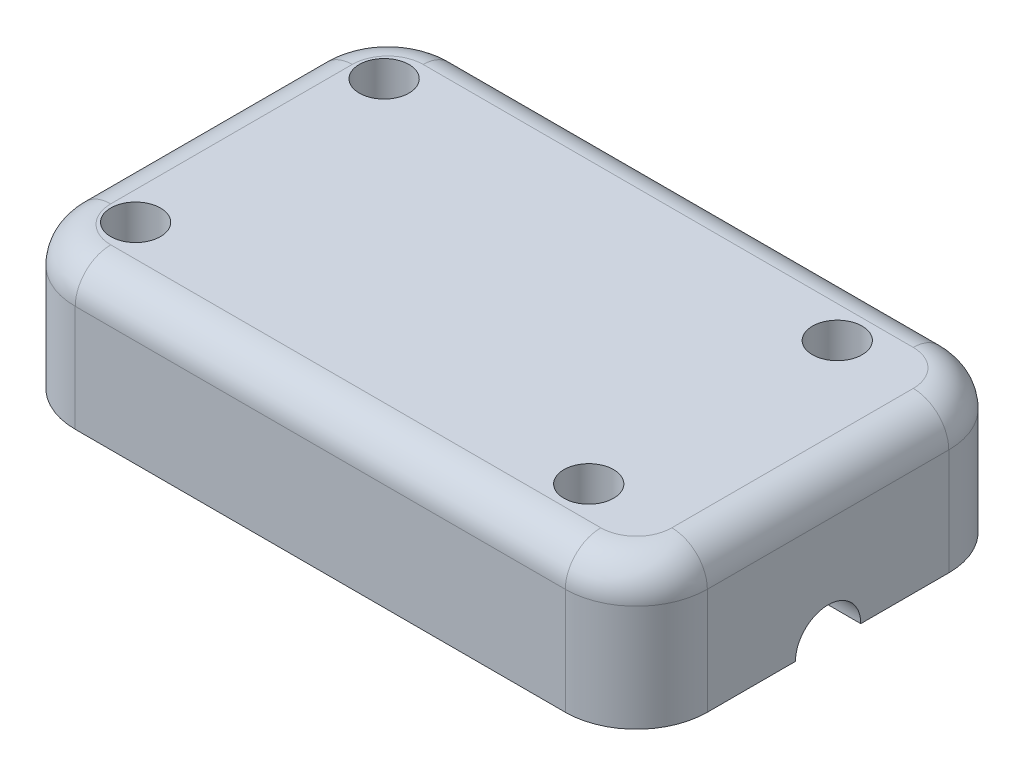
SolidWorks part; units mm, degrees
ref_plane "Front Plane" through (0, 0, 0) normal (0, 0, 1) x (1, 0, 0)
ref_plane "Top Plane" through (0, 0, 0) normal (0, 1, 0) x (1, 0, 0)
ref_plane "Right Plane" through (0, 0, 0) normal (1, 0, 0) x (0, 0, -1)
sketch "Sketch1" plane through (-2.183, 0, 0) normal (1, 0, 0) x (0, 0, -1)
  line L0 (30.2029, 27.775) -> (30.2029, 26.275) construction
  line L1 (72.2029, 27.775) -> (72.2029, 26.275) construction
  line L2 (30.2029, 27.775) -> (30.2029, 26.275)
  line L3 (72.2029, 27.775) -> (72.2029, 26.275)
  line L4 (51.2113, 25.275) -> (30.2029, 25.275)
  line L5 (51.2113, 25.275) -> (72.2029, 25.275)
  line L6 (52.7529, 43.575) -> (53.6129, 43.575) construction
  line L7 (52.7529, 43.575) -> (53.6129, 43.575)
  line L8 (72.2029, 25.275) -> (72.2029, 43.275)
  line L9 (72.2029, 25.275) -> (30.2029, 25.275)
  line L10 (72.2029, 25.275) -> (72.2029, 45.275)
  line L11 (72.2029, 45.275) -> (30.2029, 45.275)
  line L12 (30.2029, 25.275) -> (30.2029, 45.275)
  line L13 (30.2029, 25.275) -> (30.2029, 42.0569)
  circle A0 centre (51.2113, 25.275) radius 4.1
  circle A3 centre (51.2113, 25.275) radius 4.1
  circle A4 centre (51.2113, 25.275) radius 4.6
  dimension "D1" = 0.5
extrude "Boss-Extrude1" add sketch "Sketch1" along normal blind 5
sketch "Sketch3" plane through (0, 45.275, 0) normal (0, 1, 0) x (1, 0, 0)
  line L0 (2.817, 30.2029) -> (2.817, 24.2029)
  line L1 (2.817, 72.2029) -> (2.817, 78.2029)
  line L2 (-80.1986, 72.2029) -> (-80.1986, 30.2029) construction
  line L3 (-80.1986, 72.2029) -> (-80.1986, 30.2029)
  line L5 (2.817, 24.2029) -> (-81.1986, 24.2029)
  line L6 (2.817, 24.2029) -> (2.817, 78.2029)
  line L7 (2.817, 78.2029) -> (-81.1986, 78.2029)
  line L8 (-81.1986, 24.2029) -> (-81.1986, 78.2029)
  line L10 (-81.1986, 73.3472) -> (-81.1986, 73.3455)
  line L12 (-82.215, 73.3472) -> (-82.215, 73.3455)
  line L13 (-81.1986, 24.2029) -> (-86.1986, 24.2029)
  line L14 (-81.1986, 24.2029) -> (-81.1986, 78.2029)
  line L15 (-81.1986, 78.2029) -> (-86.1986, 78.2029)
  line L16 (-86.1986, 24.2029) -> (-86.1986, 78.2029)
  circle A0 centre (-13.383, 33.7029) radius 1.5 construction
  circle A1 centre (-13.383, 68.7029) radius 1.5 construction
  circle A2 centre (-77.1986, 33.7029) radius 1.5 construction
  circle A3 centre (-77.1986, 68.7029) radius 1.5 construction
  circle A4 centre (-13.383, 33.7029) radius 1.5
  circle A5 centre (-13.383, 68.7029) radius 1.5
  circle A6 centre (-77.1986, 33.7029) radius 1.5
  circle A7 centre (-77.1986, 68.7029) radius 1.5
  circle A8 centre (-13.383, 68.7029) radius 1.75
  circle A9 centre (-13.383, 33.7029) radius 1.75
  circle A10 centre (-77.1986, 33.7029) radius 1.75
  circle A11 centre (-77.1986, 68.7029) radius 1.75
  dimension "D1" = 1
extrude "Boss-Extrude2" add sketch "Sketch3" along normal blind 10
sketch "Sketch4" plane through (0, 0, -24.2029) normal (0, 0, 1) x (1, 0, 0)
  line L1 (2.817, 25.275) -> (-86.1986, 25.275)
  line L2 (2.817, 25.275) -> (2.817, 55.275)
  line L3 (2.817, 55.275) -> (-86.1986, 55.275)
  line L4 (-2.183, 45.275) -> (-2.183, 25.275)
  line L5 (-2.183, 25.275) -> (2.817, 25.275)
  line L6 (2.817, 25.275) -> (2.817, 45.275)
  line L7 (2.817, 45.275) -> (-2.183, 45.275)
  line L8 (-2.183, 45.275) -> (-2.183, 25.275)
  line L9 (-2.183, 25.275) -> (2.817, 25.275)
  line L10 (2.817, 25.275) -> (2.817, 45.275)
  line L11 (2.817, 45.275) -> (-2.183, 45.275)
  line L12 (-86.1986, 45.275) -> (2.817, 45.275)
  line L13 (2.817, 45.275) -> (2.817, 55.275)
  line L14 (2.817, 55.275) -> (-86.1986, 55.275)
  line L15 (-86.1986, 55.275) -> (-86.1986, 45.275)
  line L16 (-86.1986, 45.275) -> (2.817, 45.275)
  line L17 (2.817, 45.275) -> (2.817, 55.275)
  line L18 (2.817, 55.275) -> (-86.1986, 55.275)
  line L19 (-86.1986, 55.275) -> (-86.1986, 45.275)
  line L20 (-86.1986, 25.275) -> (-86.1986, 55.275)
  line M13 (-86.1986, 45.275) -> (2.817, 45.275)
  dimension "D1" = 0
  dimension "D2" = 0
extrude "Boss-Extrude3" add sketch "Sketch4" against normal blind 5 contours L8 L1 L2 M13 | L20 L1 L8 M13
sketch "Sketch5" plane through (0, 0, -78.2029) normal (0, 0, -1) x (-1, 0, 0)
  line L0 (2.183, 25.275) -> (2.183, 45.275) construction
  line L1 (2.183, 45.275) -> (-2.817, 45.275) construction
  line L2 (-2.817, 45.275) -> (-2.817, 25.275) construction
  line L3 (-2.817, 25.275) -> (2.183, 25.275) construction
  line L4 (-2.817, 45.275) -> (86.1986, 45.275) construction
  line L5 (86.1986, 45.275) -> (86.1986, 55.275) construction
  line L6 (86.1986, 55.275) -> (-2.817, 55.275) construction
  line L7 (-2.817, 55.275) -> (-2.817, 45.275) construction
  line L8 (2.183, 25.275) -> (2.183, 45.275)
  line L9 (2.183, 45.275) -> (-2.817, 45.275)
  line L10 (-2.817, 45.275) -> (-2.817, 25.275)
  line L11 (-2.817, 25.275) -> (2.183, 25.275)
  line L12 (-2.817, 45.275) -> (86.1986, 45.275)
  line L13 (86.1986, 45.275) -> (86.1986, 55.275)
  line L14 (86.1986, 55.275) -> (-2.817, 55.275)
  line L15 (-2.817, 55.275) -> (-2.817, 45.275)
  line L17 (-2.817, 25.275) -> (86.1986, 25.275)
  line L18 (-2.817, 25.275) -> (-2.817, 55.275)
  line L19 (-2.817, 55.275) -> (86.1986, 55.275)
  line L20 (86.1986, 25.275) -> (86.1986, 55.275)
  line M5 (-2.817, 45.275) -> (86.1986, 45.275)
extrude "Boss-Extrude4" add sketch "Sketch5" against normal blind 5 contours L17 L20 L8 M5 | L10 L11 L8 M5
sketch "Sketch6" plane through (0, 0, -72.2029) normal (0, 0, -1) x (-1, 0, 0)
  line L4 (2.183, 25.275) -> (2.183, 45.275)
  line L5 (2.183, 45.275) -> (-2.817, 45.275)
  line L6 (-2.817, 45.275) -> (-2.817, 25.275)
  line L7 (-2.817, 25.275) -> (2.183, 25.275)
  line L8 (2.183, 25.275) -> (2.183, 45.275)
  line L9 (2.183, 45.275) -> (-2.817, 45.275)
  line L10 (-2.817, 45.275) -> (-2.817, 25.275)
  line L11 (-2.817, 25.275) -> (2.183, 25.275)
  dimension "D1" = 0
extrude "Boss-Extrude5" add sketch "Sketch6" along normal blind 5
sketch "Sketch7" plane through (0, 0, -30.2029) normal (0, 0, 1) x (1, 0, 0)
  line L4 (-2.183, 45.275) -> (-2.183, 25.275)
  line L5 (-2.183, 25.275) -> (2.817, 25.275)
  line L6 (2.817, 25.275) -> (2.817, 45.275)
  line L7 (2.817, 45.275) -> (-2.183, 45.275)
  line L8 (-2.183, 45.275) -> (-2.183, 25.275)
  line L9 (-2.183, 25.275) -> (2.817, 25.275)
  line L10 (2.817, 25.275) -> (2.817, 45.275)
  line L11 (2.817, 45.275) -> (-2.183, 45.275)
  dimension "D1" = 0
extrude "Boss-Extrude6" add sketch "Sketch7" along normal blind 5
sketch "Sketch8" plane through (0, 45.275, 0) normal (0, -1, 0) x (1, 0, 0)
  line L1 (-86.1986, -29.2029) -> (-81.1986, -29.2029)
  line L2 (-86.1986, -29.2029) -> (-86.1986, -73.2029)
  line L3 (-86.1986, -73.2029) -> (-81.1986, -73.2029)
  line L4 (-2.183, -73.2029) -> (-2.183, -29.2029)
  line L5 (-2.183, -29.2029) -> (-86.1986, -29.2029)
  line L6 (-86.1986, -29.2029) -> (-86.1986, -73.2029)
  line L7 (-86.1986, -73.2029) -> (-2.183, -73.2029)
  line L8 (-2.183, -73.2029) -> (-2.183, -29.2029)
  line L9 (-2.183, -29.2029) -> (-86.1986, -29.2029)
  line L10 (-86.1986, -29.2029) -> (-86.1986, -73.2029)
  line L11 (-86.1986, -73.2029) -> (-2.183, -73.2029)
  line L12 (-81.1986, -29.2029) -> (-81.1986, -73.2029)
  line M10 (-2.183, -29.2029) -> (-86.1986, -29.2029)
  line M11 (-86.1986, -29.2029) -> (-86.1986, -73.2029)
  line M12 (-86.1986, -73.2029) -> (-2.183, -73.2029)
  dimension "D1" = 0
extrude "Boss-Extrude7" add sketch "Sketch8" along normal up to surface (20 mm away) contours L12 M10 M11 M12 up to face at (-28.5216, 25.275, -33.339)
sketch "Sketch11" plane through (0, 55.275, 0) normal (0, 1, 0) x (1, 0, 0)
  line L4 (-86.1986, 24.2029) -> (2.817, 24.2029)
  line L5 (2.817, 24.2029) -> (2.817, 78.2029)
  line L6 (2.817, 78.2029) -> (-86.1986, 78.2029)
  line L7 (-86.1986, 78.2029) -> (-86.1986, 24.2029)
  line L8 (-86.1986, 24.2029) -> (2.817, 24.2029)
  line L9 (2.817, 24.2029) -> (2.817, 78.2029)
  line L10 (2.817, 78.2029) -> (-86.1986, 78.2029)
  line L11 (-86.1986, 78.2029) -> (-86.1986, 24.2029)
  dimension "D1" = 0
extrude "Cut-Extrude2" cut sketch "Sketch11" against normal up to surface (10 mm away)
sketch "Sketch12" plane through (0, 45.275, 0) normal (0, 1, 0) x (1, 0, 0)
  circle A0 centre (-77.1986, 33.7029) radius 1.5 construction
  circle A1 centre (-77.1986, 68.7029) radius 1.5 construction
  circle A2 centre (-13.383, 68.7029) radius 1.5 construction
  circle A3 centre (-13.383, 33.7029) radius 1.5 construction
  circle A4 centre (-77.1986, 33.7029) radius 1.5
  circle A5 centre (-77.1986, 68.7029) radius 1.5
  circle A6 centre (-13.383, 68.7029) radius 1.5
  circle A7 centre (-13.383, 33.7029) radius 1.5
  circle A8 centre (-13.383, 68.7029) radius 6.1
  circle A9 centre (-13.383, 33.7029) radius 6.1
  circle A10 centre (-77.1986, 68.7029) radius 6.1
  circle A11 centre (-77.1986, 33.7029) radius 6.1
  circle A12 centre (-13.383, 33.7029) radius 1.75
  circle A13 centre (-13.383, 68.7029) radius 1.75
  circle A14 centre (-77.1986, 33.7029) radius 1.75
  circle A15 centre (-77.1986, 68.7029) radius 1.75
  line M6 (-81.1986, 29.2029) -> (-81.1986, 73.2029)
  line M7 (-81.1986, 73.2029) -> (-2.183, 73.2029)
  line M9 (-2.183, 29.2029) -> (-81.1986, 29.2029)
  line M10 (-81.1986, 29.2029) -> (-81.1986, 73.2029)
extrude "Boss-Extrude8" add sketch "Sketch12" against normal up to surface (17.5 mm away) contours A11 A14 M9 M10 | A10 A15 M6 M7 | A9 A12 M9 | A8 A13 M7
sketch "Sketch13" plane through (0, 45.275, 0) normal (0, 1, 0) x (1, 0, 0)
  line L0 (-9.2648, 73.2029) -> (-17.5013, 73.2029)
  line L1 (-73.0804, 73.2029) -> (-81.1986, 73.2029)
  line L2 (-81.1986, 73.2029) -> (-81.1986, 64.0975)
  line L3 (-73.0804, 29.2029) -> (-81.1986, 29.2029)
  line L4 (-81.1986, 29.2029) -> (-81.1986, 38.3083)
  line L5 (-9.2648, 29.2029) -> (-17.5013, 29.2029)
  arc A0 (-73.0804, 29.2029) -> (-81.1986, 38.3083) centre (-77.1986, 33.7029) ccw construction
  arc A1 (-81.1986, 64.0975) -> (-73.0804, 73.2029) centre (-77.1986, 68.7029) ccw construction
  arc A2 (-9.2648, 29.2029) -> (-17.5013, 29.2029) centre (-13.383, 33.7029) ccw construction
  arc A3 (-17.5013, 73.2029) -> (-9.2648, 73.2029) centre (-13.383, 68.7029) ccw construction
  arc A4 (-73.0804, 29.2029) -> (-81.1986, 38.3083) centre (-77.1986, 33.7029) ccw
  arc A5 (-81.1986, 64.0975) -> (-73.0804, 73.2029) centre (-77.1986, 68.7029) ccw
  arc A6 (-9.2648, 29.2029) -> (-17.5013, 29.2029) centre (-13.383, 33.7029) ccw
  arc A7 (-17.5013, 73.2029) -> (-9.2648, 73.2029) centre (-13.383, 68.7029) ccw
sketch "Sketch15" plane through (-86.1986, 0, 0) normal (-1, 0, 0) x (0, 0, 1)
  line L0 (-78.2029, 25.275) -> (-24.2029, 25.275) construction
  line L2 (-78.2029, 25.275) -> (-24.2029, 25.275) construction
  line L3 (-47.2029, 25.275) -> (-55.2029, 25.275)
  line L5 (-55.2029, 25.275) -> (-47.2029, 25.275)
  line L6 (-55.2029, 25.275) -> (-55.2029, 28.275)
  line L7 (-55.2029, 28.275) -> (-47.2029, 28.275)
  line L8 (-47.2029, 25.275) -> (-47.2029, 28.275)
  point P5 (-51.2029, 25.275)
  line M6 (-78.2029, 25.275) -> (-24.2029, 25.275)
extrude "Cut-Extrude4" cut sketch "Sketch15" against normal blind 10 contours L8 L7 L6 M6
sketch "Sketch17" plane through (0, 45.275, 0) normal (0, 1, 0) x (1, 0, 0)
  line L0 (-41.1786, 59.2029) -> (-74.1986, 59.2029) construction
  line L1 (-86.1986, 78.2029) -> (2.817, 78.2029)
  line L2 (-86.1986, 78.2029) -> (-86.1986, 24.2029)
  line L3 (-86.1986, 24.2029) -> (2.817, 24.2029)
  line L4 (2.817, 78.2029) -> (2.817, 24.2029)
  line L5 (-74.1986, 41.4229) -> (-41.1786, 41.4229) construction
  line L6 (-41.1786, 41.4229) -> (-41.1786, 59.2029) construction
  line L7 (-41.1786, 41.4229) -> (-41.1786, 59.2029)
  line L8 (-74.1986, 41.4229) -> (-41.1786, 41.4229)
  line L9 (-41.1786, 59.2029) -> (-74.1986, 59.2029)
  line L10 (-74.1986, 40.4229) -> (-40.1786, 40.4229)
  line L11 (-40.1786, 40.4229) -> (-40.1786, 60.2029)
  line L12 (-40.1786, 60.2029) -> (-74.1986, 60.2029)
  line L13 (-74.1986, 60.2029) -> (-81.1986, 60.2029)
  line L14 (-81.1986, 38.3083) -> (-81.1986, 64.0975) construction
  line L15 (-74.1986, 40.4229) -> (-81.1986, 40.4229)
  line L16 (-81.1986, 40.4229) -> (-81.1986, 60.2029)
  circle A0 centre (-77.1986, 68.7029) radius 1.75 construction
  circle A1 centre (-77.1986, 33.7029) radius 1.75 construction
  circle A2 centre (-13.383, 33.7029) radius 1.75 construction
  circle A3 centre (-13.383, 68.7029) radius 1.75 construction
  circle A4 centre (-13.383, 68.7029) radius 1.75
  circle A5 centre (-77.1986, 68.7029) radius 1.75
  circle A6 centre (-77.1986, 33.7029) radius 1.75
  circle A7 centre (-13.383, 33.7029) radius 1.75
  arc M14 (-81.1986, 64.0975) -> (-73.0804, 73.2029) centre (-77.1986, 68.7029) ccw
  line M15 (-73.0804, 73.2029) -> (-17.5013, 73.2029)
  arc M16 (-17.5013, 73.2029) -> (-9.2648, 73.2029) centre (-13.383, 68.7029) ccw
  line M17 (-9.2648, 73.2029) -> (-2.183, 73.2029)
  line M18 (-2.183, 73.2029) -> (-2.183, 29.2029)
  line M19 (-2.183, 29.2029) -> (-9.2648, 29.2029)
  arc M20 (-9.2648, 29.2029) -> (-17.5013, 29.2029) centre (-13.383, 33.7029) ccw
  line M21 (-17.5013, 29.2029) -> (-73.0804, 29.2029)
  arc M22 (-73.0804, 29.2029) -> (-81.1986, 38.3083) centre (-77.1986, 33.7029) ccw
  line M23 (-81.1986, 38.3083) -> (-81.1986, 64.0975)
  dimension "D1" = 1
extrude "Boss-Extrude9" add sketch "Sketch17" against normal blind 5 contours L10 L15 L13 L12 L11 M23 M22 M21 M20 M19 M18 M17 M16 M15 M14
sketch "Sketch18" plane through (0, 45.275, 0) normal (0, 1, 0) x (1, 0, 0)
  line L0 (-81.1986, 40.4229) -> (-81.1986, 60.2029) construction
  line L1 (-81.1986, 40.4229) -> (-40.1786, 40.4229) construction
  line L2 (-40.1786, 40.4229) -> (-40.1786, 60.2029) construction
  line L3 (-40.1786, 60.2029) -> (-81.1986, 60.2029) construction
  line L4 (-81.1986, 40.4229) -> (-81.1986, 60.2029)
  line L5 (-81.1986, 40.4229) -> (-40.1786, 40.4229)
  line L6 (-40.1786, 40.4229) -> (-40.1786, 60.2029)
  line L7 (-40.1786, 60.2029) -> (-81.1986, 60.2029)
extrude "Boss-Extrude10" add sketch "Sketch18" against normal blind 2
sketch "Sketch19" plane through (0, 45.275, 0) normal (0, 1, 0) x (1, 0, 0)
  circle A0 centre (-13.383, 33.7029) radius 1.75 construction
  circle A1 centre (-13.383, 68.7029) radius 1.75 construction
  circle A2 centre (-77.1986, 33.7029) radius 1.75 construction
  circle A3 centre (-77.1986, 68.7029) radius 1.75 construction
  circle A4 centre (-13.383, 33.7029) radius 1.75
  circle A5 centre (-13.383, 68.7029) radius 1.75
  circle A6 centre (-77.1986, 33.7029) radius 1.75
  circle A7 centre (-77.1986, 68.7029) radius 1.75
  circle A8 centre (-77.1986, 68.7029) radius 3.5
  circle A9 centre (-77.1986, 33.7029) radius 3.5
  circle A10 centre (-13.383, 68.7029) radius 3.5
  circle A11 centre (-13.383, 33.7029) radius 3.5
extrude "Cut-Extrude5" cut sketch "Sketch19" against normal blind 5
fillet "Fillet1" radius 10 4 edges at (-86.1986, 35.275, -24.2029) (2.817, 35.275, -24.2029) (2.817, 35.275, -78.2029) (-86.1986, 35.275, -78.2029)
fillet "Fillet2" radius 5 8 edges at (-0.1119, 45.275, -75.274) (-41.6908, 45.275, -78.2029) (-83.2697, 45.275, -75.274) (-86.1986, 45.275, -51.2029) (-83.2697, 45.275, -27.1318) (-41.6908, 45.275, -24.2029) (-0.1119, 45.275, -27.1318) (2.817, 45.275, -51.2029)
sketch "Sketch20" plane through (0, 40.275, 0) normal (0, -1, 0) x (1, 0, 0)
  line L0 (-3.583, -57.2029) -> (-5.183, -57.2029) construction
  line L1 (-3.583, -45.2029) -> (-5.183, -45.2029) construction
  line L2 (-3.583, -45.2029) -> (-5.183, -45.2029)
  line L3 (-3.583, -57.2029) -> (-5.183, -57.2029)
  line L4 (-2.183, -45.2029) -> (-5.183, -45.2029)
  line L5 (-2.183, -73.2029) -> (-2.183, -29.2029) construction
  line L6 (-5.183, -45.2029) -> (-4.683, -45.2029)
  line L7 (-2.183, -45.2029) -> (-2.183, -43.2029)
  line L8 (-4.683, -45.2029) -> (-2.183, -45.2029)
  line L9 (-4.683, -45.2029) -> (-4.683, -57.2029)
  line L10 (-4.683, -57.2029) -> (-2.183, -57.2029)
  line L11 (-2.183, -45.2029) -> (-2.183, -57.2029)
  line L12 (-4.683, -57.2029) -> (-4.683, -59.2029)
  line L13 (-4.683, -59.2029) -> (-6.683, -59.2029)
  line L15 (-2.183, -43.2029) -> (-6.683, -43.2029)
  line L16 (-2.183, -43.2029) -> (-2.183, -59.2029)
  line L17 (-2.183, -59.2029) -> (-6.683, -59.2029)
  line L18 (-6.683, -43.2029) -> (-6.683, -59.2029)
  line M16 (-2.183, -73.2029) -> (-2.183, -29.2029)
  dimension "D1" = 2.5
extrude "Boss-Extrude11" add sketch "Sketch20" along normal blind 12 contours L15 L18 L13 L12 L9 L6 L2 L4 M16 | L17 L10 L3 L12 M16
sketch "Sketch21" plane through (0, 40.275, 0) normal (0, -1, 0) x (1, 0, 0)
  line L4 (-4.683, -45.2029) -> (-4.683, -57.2029)
  line L5 (-4.683, -57.2029) -> (-2.183, -57.2029)
  line L6 (-2.183, -57.2029) -> (-2.183, -45.2029)
  line L7 (-2.183, -45.2029) -> (-4.683, -45.2029)
  line L8 (-4.683, -45.2029) -> (-4.683, -57.2029)
  line L9 (-4.683, -57.2029) -> (-2.183, -57.2029)
  line L10 (-2.183, -57.2029) -> (-2.183, -45.2029)
  line L11 (-2.183, -45.2029) -> (-4.683, -45.2029)
  dimension "D1" = 0
extrude "Boss-Extrude12" add sketch "Sketch21" along normal up to surface (7 mm away) separate body
sketch "Sketch22" plane through (0, 40.275, 0) normal (0, -1, 0) x (1, 0, 0)
  line L0 (-13.383, -62.6029) -> (-50013.383, -62.6029) construction
  line L1 (-6.683, -59.2029) -> (-6.683, 49940.7971) construction
  line L3 (-6.683, -62.6029) -> (-26.5743, -62.6029)
  line L4 (-6.683, -62.6029) -> (-6.683, -43.2029)
  line L5 (-6.683, -43.2029) -> (-26.5743, -43.2029)
  line L6 (-26.5743, -62.6029) -> (-26.5743, -43.2029)
  line L14 (-6.683, -43.2029) -> (-2.183, -43.2029)
  line L15 (-2.183, -43.2029) -> (-2.183, -29.2029)
  line L16 (-2.183, -29.2029) -> (-9.2648, -29.2029)
  line L17 (-17.5013, -29.2029) -> (-73.0804, -29.2029)
  line L18 (-81.1986, -38.3083) -> (-81.1986, -40.4229)
  line L19 (-81.1986, -40.4229) -> (-40.1786, -40.4229)
  line L20 (-40.1786, -40.4229) -> (-40.1786, -60.2029)
  line L21 (-40.1786, -60.2029) -> (-81.1986, -60.2029)
  line L22 (-81.1986, -60.2029) -> (-81.1986, -64.0975)
  line L23 (-73.0804, -73.2029) -> (-17.5013, -73.2029)
  line L24 (-9.2648, -73.2029) -> (-2.183, -73.2029)
  line L25 (-2.183, -73.2029) -> (-2.183, -59.2029)
  line L26 (-2.183, -59.2029) -> (-6.683, -59.2029)
  line L27 (-6.683, -59.2029) -> (-6.683, -43.2029)
  line L28 (-6.683, -43.2029) -> (-2.183, -43.2029)
  line L29 (-2.183, -43.2029) -> (-2.183, -29.2029)
  line L30 (-2.183, -29.2029) -> (-9.2648, -29.2029)
  line L31 (-17.5013, -29.2029) -> (-73.0804, -29.2029)
  line L32 (-81.1986, -38.3083) -> (-81.1986, -40.4229)
  line L33 (-81.1986, -40.4229) -> (-40.1786, -40.4229)
  line L34 (-40.1786, -40.4229) -> (-40.1786, -60.2029)
  line L35 (-40.1786, -60.2029) -> (-81.1986, -60.2029)
  line L36 (-81.1986, -60.2029) -> (-81.1986, -64.0975)
  line L37 (-73.0804, -73.2029) -> (-17.5013, -73.2029)
  line L38 (-9.2648, -73.2029) -> (-2.183, -73.2029)
  line L39 (-2.183, -73.2029) -> (-2.183, -59.2029)
  line L40 (-2.183, -59.2029) -> (-6.683, -59.2029)
  line L41 (-6.683, -59.2029) -> (-6.683, -43.2029)
  arc A4 (-17.5013, -29.2029) -> (-9.2648, -29.2029) centre (-13.383, -33.7029) ccw
  arc A5 (-81.1986, -38.3083) -> (-73.0804, -29.2029) centre (-77.1986, -33.7029) ccw
  arc A6 (-73.0804, -73.2029) -> (-81.1986, -64.0975) centre (-77.1986, -68.7029) ccw
  arc A7 (-9.2648, -73.2029) -> (-17.5013, -73.2029) centre (-13.383, -68.7029) ccw
  arc A8 (-17.5013, -29.2029) -> (-9.2648, -29.2029) centre (-13.383, -33.7029) ccw
  arc A9 (-81.1986, -38.3083) -> (-73.0804, -29.2029) centre (-77.1986, -33.7029) ccw
  arc A10 (-73.0804, -73.2029) -> (-81.1986, -64.0975) centre (-77.1986, -68.7029) ccw
  arc A11 (-9.2648, -73.2029) -> (-17.5013, -73.2029) centre (-13.383, -68.7029) ccw
  point P13 (-13.383, -62.6029)
  point P24 (-6.683, -62.6029)
  line M36 (-6.683, -59.2029) -> (-6.683, -43.2029)
  dimension "D1" = 0
extrude "Cut-Extrude6" cut sketch "Sketch22" against normal blind 3 contours L6 L3 L4 L5 M36
chamfer "Chamfer1" distance 2 angle 45 1 edges at (-81.1986, 28.275, -51.2029)
equation "\"`0\"=15"
